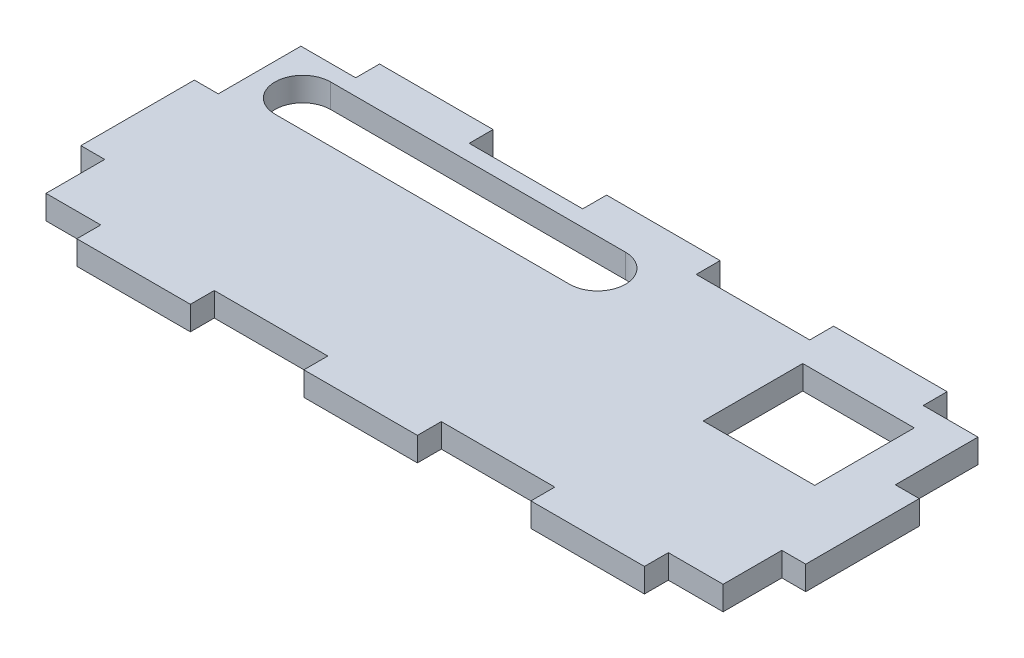
SolidWorks part; units mm, degrees
ref_plane "Front Plane" through (0, 0, 0) normal (0, 0, 1) x (1, 0, 0)
ref_plane "Top Plane" through (0, 0, 0) normal (0, 1, 0) x (1, 0, 0)
ref_plane "Right Plane" through (0, 0, 0) normal (1, 0, 0) x (0, 0, -1)
sketch "Sketch1" plane through (0, 0, 0) normal (0, 1, 0) x (1, 0, 0)
  line L44 (-42.7601, 15.0202) -> (-42.7601, 4.6452)
  line L45 (-42.7601, 4.6452) -> (-45.7601, 4.6452)
  line L46 (-45.7601, 4.6452) -> (-45.7601, -9.6048)
  line L47 (-45.7601, -9.6048) -> (-42.7601, -9.6048)
  line L48 (-42.7601, -9.6048) -> (-42.7601, -16.9798)
  line L49 (-42.7601, -16.9798) -> (-35.8851, -16.9798)
  line L50 (-35.8851, -16.9798) -> (-35.8851, -19.9798)
  line L51 (-35.8851, -19.9798) -> (-21.6351, -19.9798)
  line L52 (-21.6351, -19.9798) -> (-21.6351, -16.9798)
  line L53 (-21.6351, -16.9798) -> (-7.3851, -16.9798)
  line L54 (-7.3851, -16.9798) -> (-7.3851, -19.9798)
  line L55 (-7.3851, -19.9798) -> (6.8649, -19.9798)
  line L56 (6.8649, -19.9798) -> (6.8649, -16.9798)
  line L57 (6.8649, -16.9798) -> (21.1149, -16.9798)
  line L58 (21.1149, -16.9798) -> (21.1149, -19.9798)
  line L59 (21.1149, -19.9798) -> (35.3649, -19.9798)
  line L60 (35.3649, -19.9798) -> (35.3649, -16.9798)
  line L61 (35.3649, -16.9798) -> (42.2399, -16.9798)
  line L62 (42.2399, -16.9798) -> (42.2399, -9.6048)
  line L63 (42.2399, -9.6048) -> (45.2399, -9.6048)
  line L64 (45.2399, -9.6048) -> (45.2399, 4.6452)
  line L65 (45.2399, 4.6452) -> (42.2399, 4.6452)
  line L66 (42.2399, 4.6452) -> (42.2399, 15.0202)
  line L67 (42.2399, 15.0202) -> (35.3649, 15.0202)
  line L68 (35.3649, 15.0202) -> (35.3649, 18.0202)
  line L69 (35.3649, 18.0202) -> (21.1149, 18.0202)
  line L70 (21.1149, 18.0202) -> (21.1149, 15.0202)
  line L71 (21.1149, 15.0202) -> (6.8649, 15.0202)
  line L72 (6.8649, 15.0202) -> (6.8649, 18.0202)
  line L73 (6.8649, 18.0202) -> (-7.3851, 18.0202)
  line L74 (-7.3851, 18.0202) -> (-7.3851, 15.0202)
  line L75 (-7.3851, 15.0202) -> (-21.6351, 15.0202)
  line L76 (-21.6351, 15.0202) -> (-21.6351, 18.0202)
  line L77 (-21.6351, 18.0202) -> (-35.8851, 18.0202)
  line L78 (-35.8851, 18.0202) -> (-35.8851, 15.0202)
  line L79 (-35.8851, 15.0202) -> (-42.7601, 15.0202)
  dimension "D1" = 91
  dimension "D2" = 7.375
extrude "Boss-Extrude1" add sketch "Sketch1" along normal blind 3
sketch "Sketch2" plane through (0, 3, 0) normal (0, 1, 0) x (1, 0, 0)
  line L0 (42.2399, 15.0202) -> (35.3649, 15.0202) construction
  line L1 (23.2399, 12.0202) -> (37.2399, 12.0202)
  line L2 (23.2399, 12.0202) -> (23.2399, -0.4798)
  line L3 (23.2399, -0.4798) -> (37.2399, -0.4798)
  line L4 (37.2399, 12.0202) -> (37.2399, -0.4798)
  line L5 (42.2399, 4.6452) -> (42.2399, 15.0202) construction
  line L6 (-37, 9.4984) -> (0, 9.4984) construction
  line L7 (-37, 12.9984) -> (0, 12.9984)
  line L8 (-37, 5.9984) -> (0, 5.9984)
  arc A0 (-37, 12.9984) -> (-37, 5.9984) centre (-37, 9.4984) ccw
  arc A1 (0, 5.9984) -> (0, 12.9984) centre (0, 9.4984) ccw
  point P10 (-18.5, 9.4984)
  dimension "D6" = 3.5
  dimension "D1" = 3
  dimension "D2" = 19
  dimension "D3" = 14
  dimension "D4" = 12.5
  dimension "D5" = 37
extrude "Cut-Extrude1" cut sketch "Sketch2" against normal blind 10
